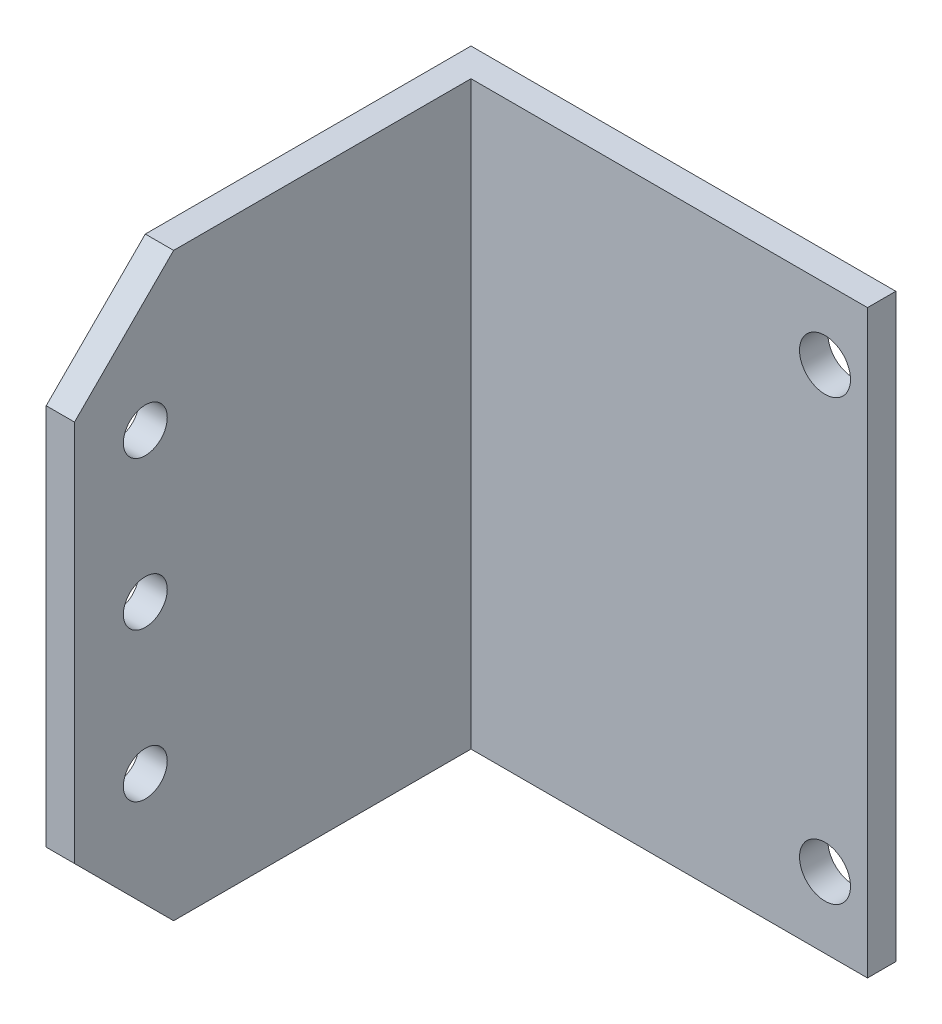
SolidWorks part; units mm, degrees
ref_plane "Front Plane" through (0, 0, 0) normal (0, 0, 1) x (1, 0, 0)
ref_plane "Top Plane" through (0, 0, 0) normal (0, 1, 0) x (1, 0, 0)
ref_plane "Right Plane" through (0, 0, 0) normal (1, 0, 0) x (0, 0, -1)
sketch "Sketch1" plane through (0, 0, 0) normal (0, 0, 1) x (1, 0, 0)
  line L0 (-3, 15.5) -> (-3, -15.5) construction
  line L1 (-3, 0) -> (0, 0) construction
  line L2 (0, 20.5) -> (-30, 20.5)
  line L3 (0, 20.5) -> (0, -20.5)
  line L4 (0, -20.5) -> (-30, -20.5)
  line L5 (-30, 20.5) -> (-30, -20.5)
  circle A0 centre (-3, 15.5) radius 1.8
  circle A1 centre (-3, -15.5) radius 1.8
  dimension "D6" = 3.6
  dimension "D1" = 3
  dimension "D2" = 30
  dimension "D3" = 5
  dimension "D4" = 31
  dimension "D5" = 5
extrude "Boss-Extrude1" add sketch "Sketch1" along normal blind 2
sketch "Sketch2" plane through (0, 0, 2) normal (0, 0, 1) x (1, 0, 0)
  line L0 (0, 20.5) -> (-30, 20.5) construction
  line L1 (-30, -20.5) -> (-28, -20.5)
  line L2 (-30, -20.5) -> (-30, 20.5)
  line L3 (-30, 20.5) -> (-28, 20.5)
  line L4 (-28, -20.5) -> (-28, 20.5)
  dimension "D1" = 2
extrude "Boss-Extrude2" add sketch "Sketch2" along normal blind 28
sketch "Sketch3" plane through (-28, 0, 0) normal (1, 0, 0) x (0, 0, -1)
  line L0 (-25, 20.5) -> (-25, -20.5) construction
  line L1 (-30, 20.5) -> (-2, 20.5) construction
  line L2 (-30, -20.5) -> (-2, -20.5) construction
  line L3 (-30, -13.5) -> (-23, -20.5)
  line L4 (-30, 13.5) -> (-30, 20.5)
  line L5 (-30, -20.5) -> (-30, 20.5) construction
  line L6 (-30, 20.5) -> (-23, 20.5)
  line L7 (-23, 20.5) -> (-30, 13.5)
  line L8 (-30, -13.5) -> (-30, -20.5)
  line L9 (-30, -20.5) -> (-23, -20.5)
  circle A0 centre (-25, 10.5) radius 1.55
  circle A1 centre (-25, -10.5) radius 1.55
  circle A2 centre (-25, 0) radius 1.55
  dimension "D4" = 3.1
  dimension "D1" = 7
  dimension "D2" = 10
  dimension "D3" = 10
  dimension "D5" = 5
extrude "Cut-Extrude1" cut sketch "Sketch3" against normal blind 10
